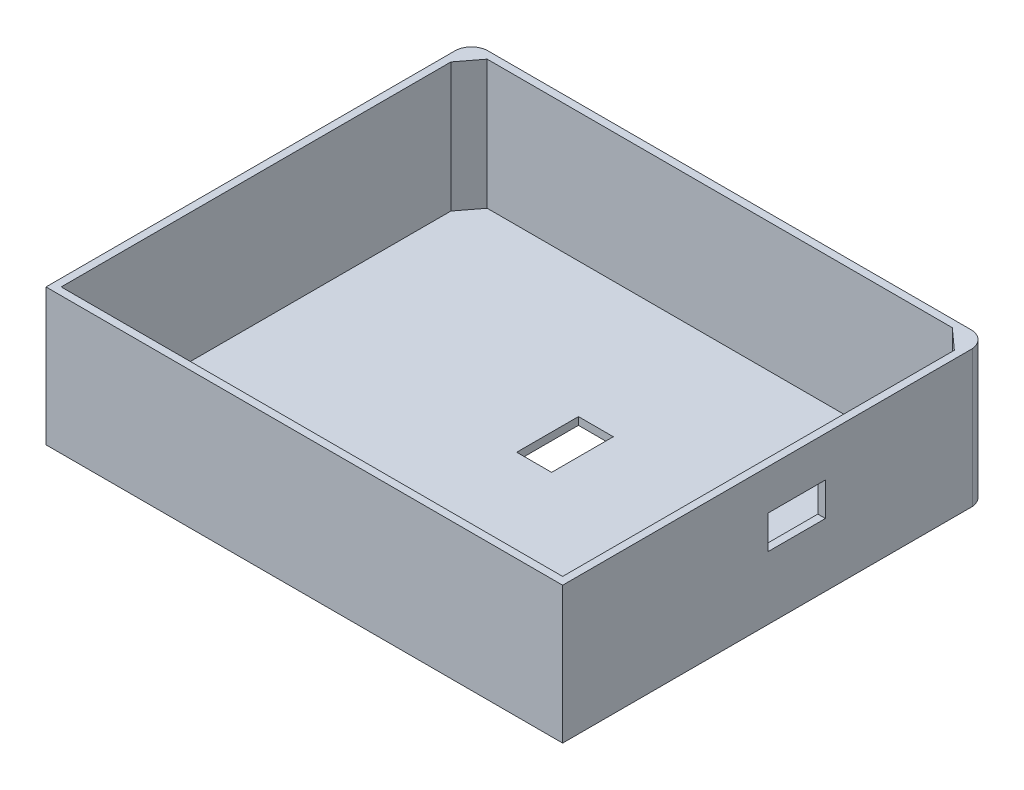
SolidWorks part; units mm, degrees
ref_plane "Front Plane" through (0, 0, 0) normal (0, 0, 1) x (1, 0, 0)
ref_plane "Top Plane" through (0, 0, 0) normal (0, 1, 0) x (1, 0, 0)
ref_plane "Right Plane" through (0, 0, 0) normal (1, 0, 0) x (0, 0, -1)
sketch "Sketch1" plane through (0, 0, 0) normal (0, 1, 0) x (1, 0, 0)
  line L0 (-15.2428, 6.7663) -> (18.7572, 6.7663)
  line L1 (18.7572, 6.7663) -> (18.7572, -21.2337)
  line L2 (18.7572, -21.2337) -> (-15.2428, -21.2337)
  line L3 (-15.2428, -21.2337) -> (-15.2428, 6.7663)
  dimension "D1" = 34
  dimension "D2" = 28
extrude "Boss-Extrude1" add sketch "Sketch1" along normal blind 9
sketch "Sketch3" plane through (0, 9, 0) normal (0, 1, 0) x (1, 0, 0)
  line L0 (18.7572, 6.7663) -> (-15.2428, 6.7663) construction
  line L1 (-13.7096, 6.2663) -> (-14.7428, 4.9163)
  line L3 (-14.7428, 4.9163) -> (-14.7428, -17.2065)
  line L4 (-14.7428, -17.2065) -> (-14.7428, -20.7337)
  line L5 (-14.7428, -20.7337) -> (18.2572, -20.7337)
  line L6 (18.2572, -20.7337) -> (18.2572, 5.0463)
  line L7 (18.2572, 5.0463) -> (16.9039, 6.2663)
  line L8 (16.9039, 6.2663) -> (-13.7096, 6.2663)
  line L9 (-15.2428, 6.7663) -> (-15.2428, -21.2337) construction
  line L10 (18.7572, -21.2337) -> (18.7572, 6.7663) construction
  line L11 (-15.2428, -21.2337) -> (18.7572, -21.2337) construction
  point P0 (-12.5428, 6.7663)
  point P1 (1.7572, 6.7663)
  point P4 (16.0572, 6.7663)
  dimension "D1" = 14.3
  dimension "D2" = 14.3
  dimension "D3" = 0.5
  dimension "D4" = 0.5
  dimension "D5" = 1.35
  dimension "D6" = 1.7
  dimension "D7" = 0.5
  dimension "D8" = 0.5
  dimension "D9" = 1.22
  dimension "D10" = 1.822
extrude "Cut-Extrude1" cut sketch "Sketch3" against normal blind 8.5
sketch "Sketch4" plane through (0, 9, 0) normal (0, 1, 0) x (1, 0, 0)
  line L0 (18.2572, 5.0463) -> (16.9039, 6.2663) construction
  line L1 (18.7572, 6.7663) -> (-15.2428, 6.7663) construction
  line L2 (-13.7096, 6.2663) -> (-14.7428, 4.9163) construction
  line L3 (-15.2428, 6.7663) -> (-15.2428, -21.2337) construction
  line L4 (-15.2428, 5.7037) -> (-15.2428, 6.7663)
  line L5 (-15.2428, 6.7663) -> (-14.1849, 6.7651)
  line L6 (18.7634, 5.6549) -> (18.7572, 6.7663)
  line L7 (18.7572, -21.2337) -> (18.7572, 6.7663) construction
  line L8 (18.7572, 6.7663) -> (17.6675, 6.7663)
  arc A0 (17.6675, 6.7663) -> (18.7634, 5.6549) centre (17.6185, 5.6221) cw
  arc A1 (-15.2428, 5.7037) -> (-14.1849, 6.7651) centre (-14.1581, 5.6804) cw
extrude "Cut-Extrude2" cut sketch "Sketch4" against normal blind 9
sketch "Sketch5" plane through (0, 9, 0) normal (0, 1, 0) x (1, 0, 0)
  line L0 (-14.1849, 6.7651) -> (-14.1812, 6.7663)
  line L1 (17.6675, 6.7663) -> (-15.2428, 6.7663) construction
  line L2 (-14.1812, 6.7663) -> (-15.3743, 6.8209)
  line L3 (-15.3743, 6.8209) -> (-15.3303, 6.6611)
  line L4 (-15.3303, 6.6611) -> (-14.1849, 6.7651)
extrude "Cut-Extrude3" cut sketch "Sketch5" against normal blind 9
sketch "Sketch6" plane through (0, 0.5, 0) normal (0, 1, 0) x (1, 0, 0)
  line L1 (1.1669, -2.6039) -> (3.4629, -2.6039)
  line L2 (1.1669, -2.6039) -> (1.1669, -6.6651)
  line L3 (1.1669, -6.6651) -> (3.4629, -6.6651)
  line L4 (3.4629, -2.6039) -> (3.4629, -6.6651)
  line L5 (1.1669, -2.6039) -> (3.4629, -6.6651) construction
  line L6 (1.1669, -6.6651) -> (3.4629, -2.6039) construction
  point P0 (2.3149, -4.6345)
extrude "Cut-Extrude4" cut sketch "Sketch6" against normal blind 9
sketch "Sketch7" plane through (18.7572, 0, 0) normal (1, 0, 0) x (0, 0, -1)
  line L1 (-7.7044, 6.3515) -> (-3.9386, 6.3515)
  line L2 (-7.7044, 6.3515) -> (-7.7044, 4.1548)
  line L3 (-7.7044, 4.1548) -> (-3.9386, 4.1548)
  line L4 (-3.9386, 6.3515) -> (-3.9386, 4.1548)
  line L5 (-7.7044, 6.3515) -> (-3.9386, 4.1548) construction
  line L6 (-7.7044, 4.1548) -> (-3.9386, 6.3515) construction
  point P0 (-5.8215, 5.2532)
extrude "Cut-Extrude5" cut sketch "Sketch7" against normal blind 9
